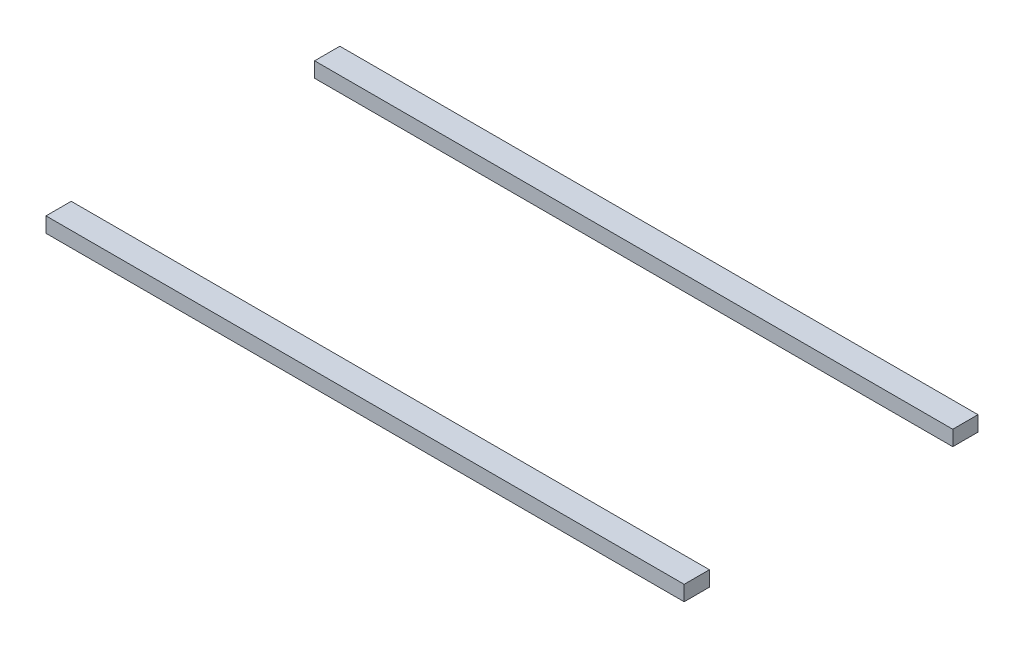
SolidWorks part; units mm, degrees
ref_plane "Alzado" through (0, 0, 0) normal (0, 0, 1) x (1, 0, 0)
ref_plane "Planta" through (0, 0, 0) normal (0, 1, 0) x (1, 0, 0)
ref_plane "Vista lateral" through (0, 0, 0) normal (1, 0, 0) x (0, 0, -1)
sketch "Croquis1" plane through (0, 0, 0) normal (0, 1, 0) x (1, 0, 0)
  line L0 (-632, 241) -> (632, 241)
  line L1 (-632, -291) -> (632, -291)
  line L2 (-632, -291) -> (-632, 291)
  line L3 (-632, 291) -> (632, 291)
  line L4 (632, -291) -> (632, 291)
  line L5 (-632, -291) -> (632, 291) construction
  line L6 (-632, 291) -> (632, -291) construction
  line L7 (-632, -241) -> (632, -241)
  line L8 (-632, 0) -> (632, 0) construction
  point P0 (0, 0)
  dimension "D1" = 582
  dimension "D2" = 1264
  dimension "D3" = 50
extrude "Saliente-Extruir1" add sketch "Croquis1" along normal blind 30 contours L7 L2 L1 L4 | L0 L4 L3 L2
